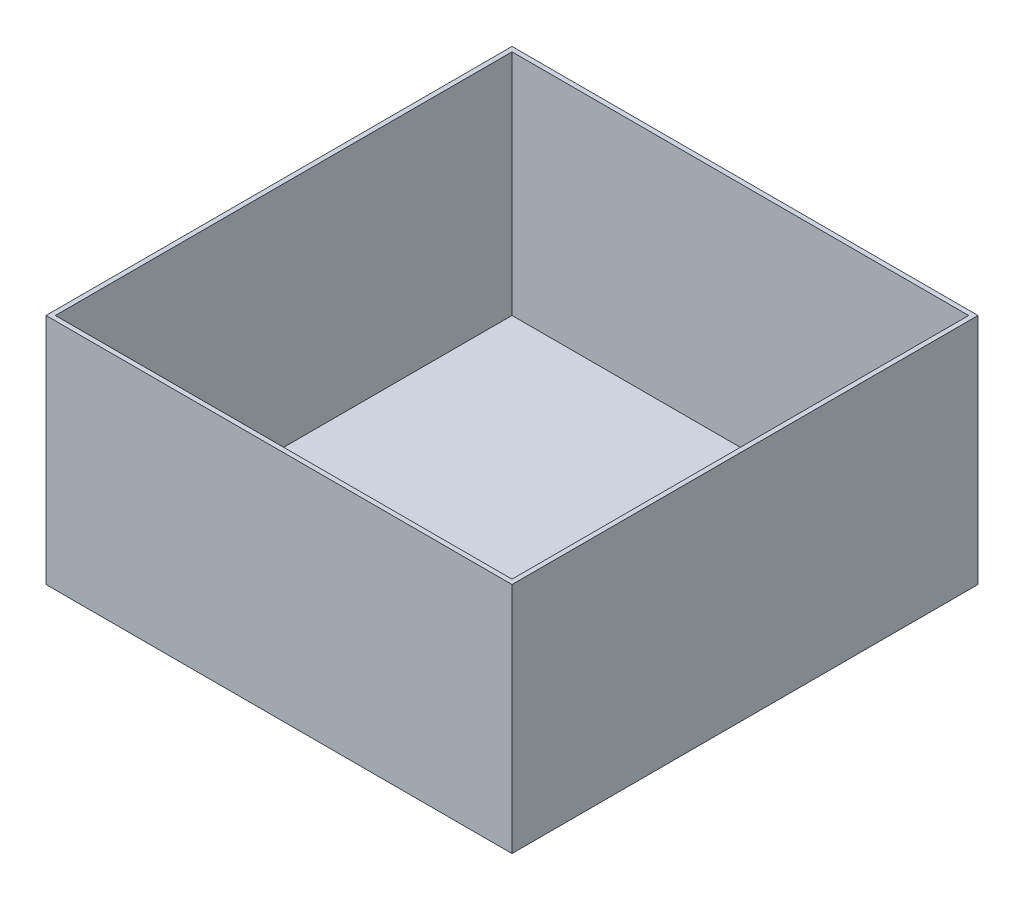
SolidWorks part; units mm, degrees
ref_plane "Front" through (0, 0, 0) normal (0, 0, 1) x (1, 0, 0)
ref_plane "Top" through (0, 0, 0) normal (0, 1, 0) x (1, 0, 0)
ref_plane "Right" through (0, 0, 0) normal (1, 0, 0) x (0, 0, -1)
sketch "草图1" plane through (0, 0, 0) normal (0, 0, 1) x (1, 0, 0)
  line L1 (-500, 250) -> (500, 250)
  line L2 (-500, 250) -> (-500, -250)
  line L3 (-500, -250) -> (500, -250)
  line L4 (500, 250) -> (500, -250)
  line L5 (-500, 250) -> (500, -250) construction
  line L6 (-500, -250) -> (500, 250) construction
  point P1 (0, 0)
extrude "凸台-拉伸1" add sketch "草图1" along normal blind 1000
sketch "草图2" plane through (0, 250, 0) normal (0, 1, 0) x (1, 0, 0)
  line L8 (490, -10) -> (-490, -10)
  line L9 (-490, -10) -> (-490, -990)
  line L10 (-490, -990) -> (490, -990)
  line L11 (490, -990) -> (490, -10)
  line L12 (490, -10) -> (-490, -10)
  line L13 (-490, -10) -> (-490, -990)
  line L14 (-490, -990) -> (490, -990)
  line L15 (490, -990) -> (490, -10)
  dimension "D1" = 10
extrude "切除-拉伸1" cut sketch "草图2" against normal blind 490
